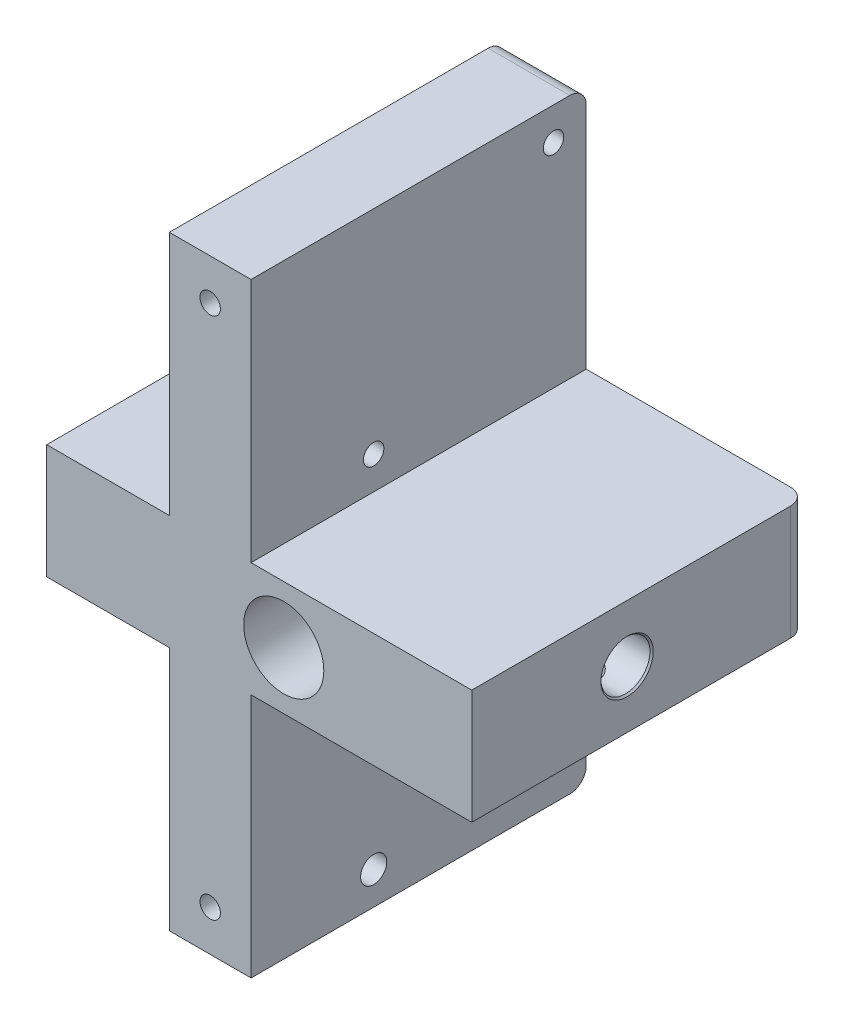
SolidWorks part; units mm, degrees
ref_plane "Face" through (0, 0, 0) normal (0, 0, 1) x (1, 0, 0)
ref_plane "Dessus" through (0, 0, 0) normal (0, 1, 0) x (1, 0, 0)
ref_plane "Droite" through (0, 0, 0) normal (1, 0, 0) x (0, 0, -1)
sketch "Esquisse1" plane through (0, 0, 0) normal (0, 0, 1) x (1, 0, 0)
  line L0 (-4, -7) -> (-4, -37)
  line L1 (-14, 37) -> (-4, 37)
  line L2 (-14, 37) -> (-14, 7)
  line L3 (-14, -37) -> (-4, -37)
  line L4 (-4, 37) -> (-4, 7)
  line L5 (-29, 7) -> (-14, 7)
  line L6 (-29, 7) -> (-29, -7)
  line L7 (-29, -7) -> (-14, -7)
  line L8 (23, 7) -> (23, -7)
  line L9 (-4, 7) -> (23, 7)
  line L10 (-14, -7) -> (-14, -37)
  line L11 (-4, -7) -> (23, -7)
  circle A0 centre (0, 0) radius 4.9
  dimension "D1" = 14
  dimension "D9" = 9.8
  dimension "D2" = 7
  dimension "D3" = 4
  dimension "D4" = 10
  dimension "D5" = 37
  dimension "D6" = 37
  dimension "D7" = 29
  dimension "D8" = 23
extrude "Boss.-Extru.1" add sketch "Esquisse1" along normal blind 19 and the other way blind 22
hole_wizard "Diamètre du perçage Ø6.0 (6)1" positions "Esquisse3" profile "Esquisse2" hole size "Ø6.0" standard "Din"
sketch "Esquisse3" plane through (23, 0, 0) normal (1, 0, 0) x (0, 0, -1)
  point P0 (0, 0)
sketch "Esquisse2" plane through (23, 0, 0) normal (0, 1, 0) x (0, 0, -1)
  line L0 (0, 0) -> (0, 11.8026)
  line L1 (0, 11.8026) -> (3, 10)
  line L2 (3, 10) -> (3, 0)
  line L5 (3, 0) -> (0, 0)
  line L10 (0, 11.8026) -> (-3, 10) construction
  line L11 (0, -6.35) -> (0, 107.95) construction
  dimension "Diamètre du perçage" = 6
  dimension "Profondeur du perçage" = 10
  dimension "Angle de pointe" = 118
sketch "Esquisse6" plane through (-4, 0, 0) normal (1, 0, 0) x (0, 0, -1)
  line L0 (-19, 11) -> (22, 11) construction
  line L1 (-19, 7) -> (-19, 37) construction
  line L2 (22, 7) -> (22, 37) construction
  line L3 (-19, -11) -> (22, -11) construction
  line L4 (-19, -37) -> (-19, -7) construction
  line L5 (22, -37) -> (22, -7) construction
  line L6 (-19, 33) -> (22, 33) construction
  line L7 (-19, -33) -> (22, -33) construction
  line L8 (-4, 33) -> (-4, -33) construction
  line L9 (18, 33) -> (18, -33) construction
  circle A0 centre (18, -11) radius 1.6
  circle A2 centre (-4, -33) radius 1.6
  dimension "D9" = 3.2
  dimension "D10" = 3.2
  dimension "D1" = 11
  dimension "D2" = 11
  dimension "D3" = 22
  dimension "D4" = 22
  dimension "D5" = 4
  dimension "D6" = 22
extrude "Enlèv. mat.-Extru.1" cut sketch "Esquisse6" against normal up to next
hole_wizard "Diamètre du perçage Ø3.0 (3)1" positions "Esquisse8" profile "Esquisse7" hole size "Ø3.0" standard "Din"
sketch "Esquisse8" plane through (-29, 0, 0) normal (-1, 0, 0) x (0, 0, 1)
  point P0 (0, 0)
sketch "Esquisse7" plane through (-29, 0, 0) normal (0, 1, 0) x (0, 0, 1)
  line L0 (0, 0) -> (0, 10.9013)
  line L1 (0, 10.9013) -> (1.5, 10)
  line L2 (1.5, 10) -> (1.5, 0)
  line L5 (1.5, 0) -> (0, 0)
  line L10 (0, 10.9013) -> (-1.5, 10) construction
  line L11 (0, -6.35) -> (0, 107.95) construction
  dimension "Diamètre du perçage" = 3
  dimension "Profondeur du perçage" = 10
  dimension "Angle de pointe" = 118
hole_wizard "Trou taraudé M31" positions "Esquisse12" profile "Esquisse11" tap size "M3" standard "Iso"
sketch "Esquisse12" plane through (0, 0, 19) normal (0, 0, 1) x (1, 0, 0)
  point P4 (-9, 32)
  point P7 (-9, -32)
  dimension "D1" = 32
  dimension "D2" = 32
  dimension "D3" = 9
  dimension "D4" = 9
sketch "Esquisse11" plane through (-9, 32, 19) normal (1, 0, 0) x (0, -1, 0)
  line L0 (0, 0) -> (0, 9.2511)
  line L1 (0, 9.2511) -> (1.25, 8.5)
  line L2 (1.25, 8.5) -> (1.25, 0)
  line L5 (1.25, 0) -> (0, 0)
  line L10 (0, 9.2511) -> (-1.25, 8.5) construction
  line L11 (0, -6.35) -> (0, 107.95) construction
  dimension "Diamètre du trou pour taraudage" = 2.5
  dimension "Profondeur du trou pour taraudage" = 8.5
  dimension "Angle de pointe" = 118
cosmetic thread "Filetage de perçage4" parameters "D1"=6, "D2"=3
cosmetic thread "Filetage de perçage6" parameters "D1"=6, "D2"=3
fillet "Congé1" radius 2 4 edges at (-9, -37, -22) (-29, 0, -22) (23, 0, -22) (-9, 37, -22)
hole_wizard "Trou taraudé M32" positions "Esquisse18" profile "Esquisse17" tap size "M3" standard "Iso"
sketch "Esquisse18" plane through (0, -7, 0) normal (0, -1, 0) x (-1, 0, 0)
  line L0 (29, 20) -> (29, -19) construction
  line L2 (4, -19) -> (-23, -19) construction
  point P0 (25, 0)
  point P11 (0, -11)
  dimension "D1" = 4
  dimension "D3" = 8
sketch "Esquisse17" plane through (-25, -7, 0) normal (1, 0, 0) x (0, 0, -1)
  line L0 (0, 0) -> (0, 5.5)
  line L1 (0, 5.5) -> (1.25, 5.5)
  line L2 (1.25, 5.5) -> (1.25, 0)
  line L5 (1.25, 0) -> (0, 0)
  line L11 (0, -6.35) -> (0, 107.95) construction
  dimension "Diamètre du trou pour taraudage jusqu'au prochain" = 2.5
  dimension "Profondeur du trou pour taraudage jusqu'au prochain" = 5.5
cosmetic thread "Filetage de perçage9" parameters "D2"=3
cosmetic thread "Filetage de perçage11" parameters "D2"=3
hole_wizard "Trou taraudé M41" positions "Esquisse20" profile "Esquisse19" tap size "M4" standard "Iso"
sketch "Esquisse20" plane through (0, -7, 0) normal (0, -1, 0) x (-1, 0, 0)
  line L0 (-23, 20) -> (-23, -19) construction
  point P0 (-18, 0)
  dimension "D1" = 5
sketch "Esquisse19" plane through (18, -7, 0) normal (1, 0, 0) x (0, 0, -1)
  line L0 (0, 0) -> (0, 4)
  line L1 (0, 4) -> (1.65, 4)
  line L2 (1.65, 4) -> (1.65, 0)
  line L5 (1.65, 0) -> (0, 0)
  line L11 (0, -6.35) -> (0, 107.95) construction
  dimension "Diamètre du trou pour taraudage jusqu'au prochain" = 3.3
  dimension "Profondeur du trou pour taraudage jusqu'au prochain" = 4
cosmetic thread "Filetage de perçage12" parameters "D2"=4
chamfer "Chanfrein1" distance 0.2 angle 45 3 edges at (-29, 0, 1.5) (23, 0, -3) (4.9, 0, -22)
hole_wizard "Trou taraudé M33" positions "Esquisse22" profile "Esquisse21" tap size "M3" standard "Iso" end condition up to next
sketch "Esquisse22" plane through (-4, 0, 0) normal (1, 0, 0) x (0, 0, -1)
  line L0 (-19, 11) -> (22, 11) construction
  line L1 (-4, 33) -> (-4, -33) construction
  point P0 (18, 33)
  point P3 (-4, 11)
cosmetic thread "Filetage de perçage13" parameters "D2"=3
cosmetic thread "Filetage de perçage14" parameters "D2"=3
sketch "Esquisse21" plane through (-4, 33, -18) normal (0, 1, 0) x (0, 0, -1)
  line L0 (0, 0) -> (0, 10)
  line L1 (0, 10) -> (1.25, 10)
  line L2 (1.25, 10) -> (1.25, 0)
  line L5 (1.25, 0) -> (0, 0)
  line L11 (0, -6.35) -> (0, 107.95) construction
  dimension "Diamètre du trou pour taraudage jusqu'au prochain" = 2.5
  dimension "Profondeur du trou pour taraudage jusqu'au prochain" = 10
